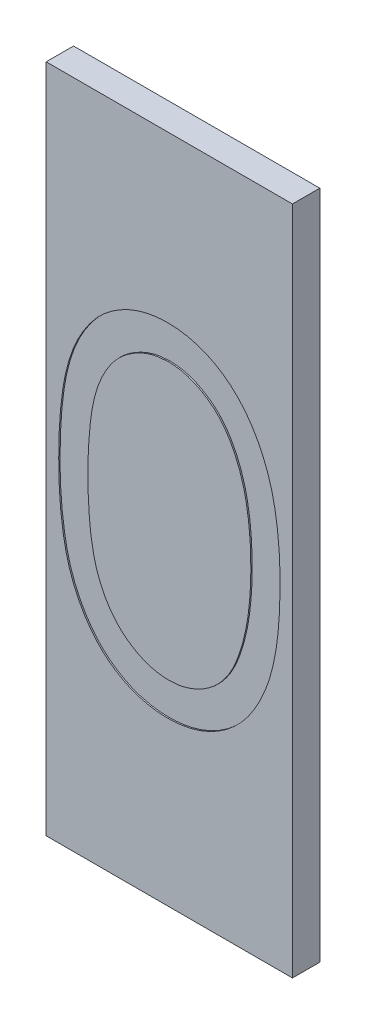
SolidWorks part; units mm, degrees
ref_plane "正面" through (0, 0, 0) normal (0, 0, 1) x (1, 0, 0)
ref_plane "平面" through (0, 0, 0) normal (0, 1, 0) x (1, 0, 0)
ref_plane "右側面" through (0, 0, 0) normal (1, 0, 0) x (0, 0, -1)
sketch "ｽｹｯﾁ1" plane through (0, 0, 0) normal (0, 0, 1) x (1, 0, 0)
  line L0 (18, 0) -> (0, 0)
  line L1 (18, 49) -> (0, 49)
  line L2 (0, 0) -> (0, 49)
  line L4 (18, 0) -> (18, 49)
extrude "ﾎﾞｽ - 押し出し1" add sketch "ｽｹｯﾁ1" along normal blind 2
sketch "ｽｹｯﾁ2" plane through (0, 0, 2) normal (0, 0, 1) x (1, 0, 0)
  text T0 "0" font "Century Gothic" height in points 90
extrude "ｶｯﾄ - 押し出し1" cut sketch "ｽｹｯﾁ2" against normal blind 0.1
